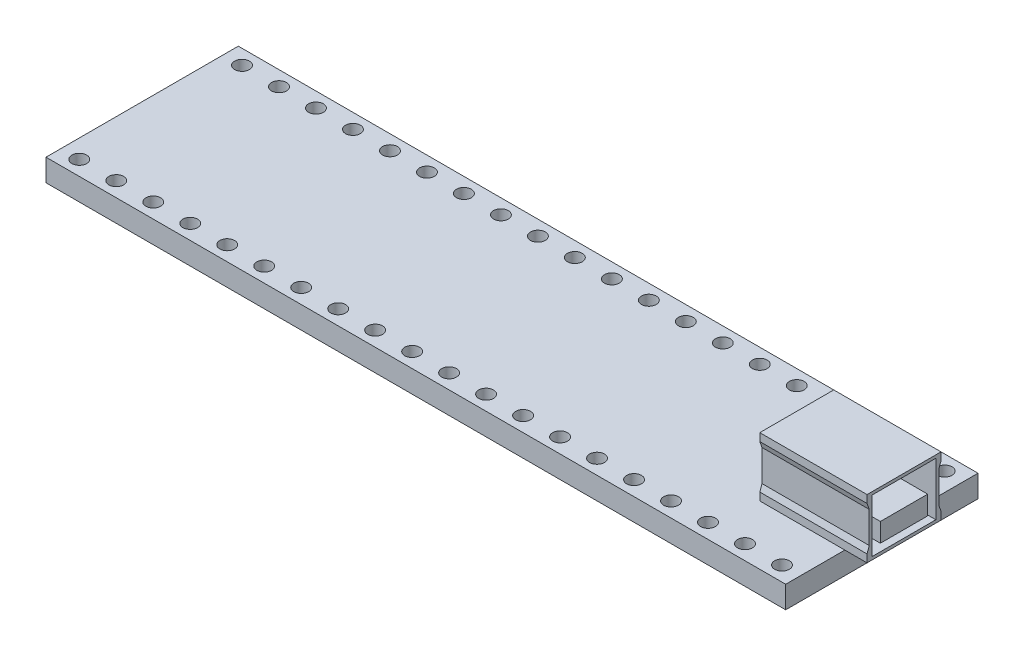
SolidWorks part; units mm, degrees
ref_plane "Спереди" through (0, 0, 0) normal (0, 0, 1) x (1, 0, 0)
ref_plane "Сверху" through (0, 0, 0) normal (0, 1, 0) x (1, 0, 0)
ref_plane "Справа" through (0, 0, 0) normal (1, 0, 0) x (0, 0, -1)
sketch "Эскиз1" plane through (0, 0, 0) normal (0, 1, 0) x (1, 0, 0)
  line L0 (-3.4531, 12) -> (49996.5469, 12) construction
  line L1 (0, 0) -> (50, 0)
  line L2 (0, 0) -> (0, 13)
  line L3 (0, 13) -> (50, 13)
  line L4 (50, 0) -> (50, 13)
  line L5 (-6.0552, 1) -> (49993.9448, 1) construction
  circle A0 centre (1.25, 12) radius 0.5
  circle A1 centre (3.75, 12) radius 0.5
  circle A2 centre (6.25, 12) radius 0.5
  circle A3 centre (8.75, 12) radius 0.5
  circle A4 centre (11.25, 12) radius 0.5
  circle A5 centre (13.75, 12) radius 0.5
  circle A6 centre (16.25, 12) radius 0.5
  circle A7 centre (18.75, 12) radius 0.5
  circle A8 centre (21.25, 12) radius 0.5
  circle A9 centre (23.75, 12) radius 0.5
  circle A10 centre (26.25, 12) radius 0.5
  circle A11 centre (28.75, 12) radius 0.5
  circle A12 centre (31.25, 12) radius 0.5
  circle A13 centre (33.75, 12) radius 0.5
  circle A14 centre (36.25, 12) radius 0.5
  circle A15 centre (3.75, 1) radius 0.5
  circle A16 centre (6.25, 1) radius 0.5
  circle A17 centre (8.75, 1) radius 0.5
  circle A18 centre (11.25, 1) radius 0.5
  circle A19 centre (13.75, 1) radius 0.5
  circle A20 centre (16.25, 1) radius 0.5
  circle A21 centre (18.75, 1) radius 0.5
  circle A22 centre (21.25, 1) radius 0.5
  circle A23 centre (23.75, 1) radius 0.5
  circle A24 centre (26.25, 1) radius 0.5
  circle A25 centre (28.75, 1) radius 0.5
  circle A26 centre (31.25, 1) radius 0.5
  circle A27 centre (33.75, 1) radius 0.5
  circle A28 centre (36.25, 1) radius 0.5
  circle A29 centre (1.25, 1) radius 0.5
  circle A30 centre (38.75, 12) radius 0.5
  circle A31 centre (41.25, 12) radius 0.5
  circle A32 centre (43.75, 12) radius 0.5
  circle A33 centre (46.25, 12) radius 0.5
  circle A34 centre (48.75, 12) radius 0.5
  circle A35 centre (38.75, 1) radius 0.5
  circle A36 centre (41.25, 1) radius 0.5
  circle A37 centre (43.75, 1) radius 0.5
  circle A38 centre (46.25, 1) radius 0.5
  circle A39 centre (48.75, 1) radius 0.5
  dimension "D5" = 1.25
  dimension "D6" = 20
  dimension "D1" = 13
  dimension "D2" = 50
  dimension "D3" = 1
  dimension "D4" = 1
  dimension "D7" = 2
extrude "Бобышка-Вытянуть1" add sketch "Эскиз1" along normal blind 1.5
sketch "Эскиз3" plane through (0, 1.5, 0) normal (0, 1, 0) x (1, 0, 0)
  line L0 (0, 6.5) -> (50, 6.5) construction
  line L1 (44.25, 9) -> (51.5, 9)
  line L2 (44.25, 9) -> (44.25, 4)
  line L3 (44.25, 4) -> (51.5, 4)
  line L4 (51.5, 9) -> (51.5, 4)
  line L5 (0, 13) -> (0, 0) construction
  line L6 (50, 0) -> (50, 13) construction
  dimension "D1" = 2.5
  dimension "D2" = 5
  dimension "D3" = 1.5
  dimension "D4" = 7.25
extrude "Бобышка-Вытянуть2" add sketch "Эскиз3" along normal blind 4
sketch "Эскиз4" plane through (0, 0, 0) normal (0, -1, 0) x (1, 0, 0)
  line L0 (50, 0) -> (50, -13) construction
  line L1 (30.75, -4) -> (38, -4)
  line L2 (30.75, -4) -> (30.75, -9.5)
  line L3 (30.75, -9.5) -> (38, -9.5)
  line L4 (38, -4) -> (38, -9.5)
  point P6 (50, -6.5)
  dimension "D1" = 7.25
  dimension "D2" = 5.5
  dimension "D3" = 12
  dimension "D4" = 2.5
extrude "Бобышка-Вытянуть3" add sketch "Эскиз4" along normal blind 3
sketch "Эскиз5" plane through (51.5, 0, 0) normal (1, 0, 0) x (0, 0, -1)
  line L0 (6.5, 5.5) -> (6.5, 1.5) construction
  line L1 (4, 5.5) -> (9, 5.5) construction
  line L2 (4, 1.5) -> (9, 1.5) construction
  line L4 (4, 4.9769) -> (4.1486, 4.5568)
  line L5 (4, 5.5) -> (4, 1.5) construction
  line L6 (4.1486, 4.5568) -> (4.1486, 3.5404)
  line L7 (4, 3.5) -> (9, 3.5) construction
  line L8 (9, 5.5) -> (9, 1.5) construction
  line L9 (4, 4.9769) -> (4, 5.5)
  line L10 (4, 5.5) -> (9, 5.5)
  line L11 (4, 1.5) -> (9, 1.5)
  line L12 (4, 2.0231) -> (4, 1.5)
  line L13 (4.1486, 2.4432) -> (4.1486, 3.4596)
  line L14 (4, 2.0231) -> (4.1486, 2.4432)
  line L15 (9, 2.0231) -> (8.8514, 2.4432)
  line L16 (8.8514, 2.4432) -> (8.8514, 3.4596)
  line L17 (9, 2.0231) -> (9, 1.5)
  line L18 (9, 4.9769) -> (9, 5.5)
  line L19 (8.8514, 4.5568) -> (8.8514, 3.5404)
  line L20 (9, 4.9769) -> (8.8514, 4.5568)
  line L21 (4.1486, 3.5404) -> (4.1486, 3.4596)
  line L22 (8.8514, 3.5404) -> (8.8514, 3.4596)
  line M2 (9, 1.5) -> (9, 5.5)
  line M4 (4, 5.5) -> (4, 1.5)
extrude "Вырез-Вытянуть1" cut sketch "Эскиз5" against normal up to surface (7.25 mm away) contours L21 L6 L4 L14 L13 M4 | L19 L22 L16 L15 L20 M2 up to face at (44.25, 3.5, -6.5)
sketch "Эскиз6" plane through (51.5, 0, 0) normal (1, 0, 0) x (0, 0, -1)
  line L0 (6.5, 5.5) -> (6.5, 1.5) construction
  line L1 (4, 5.5) -> (9, 5.5) construction
  line L2 (4, 1.5) -> (9, 1.5) construction
  line L3 (4, 1.5) -> (9, 1.5) construction
  line L4 (4.3486, 5.3) -> (8.6514, 5.3)
  line L5 (4.3486, 5.3) -> (4.3486, 1.7)
  line L6 (4.3486, 1.7) -> (8.6514, 1.7)
  line L7 (8.6514, 5.3) -> (8.6514, 1.7)
  line L8 (4.1486, 4.5568) -> (4.1486, 2.4432) construction
  line L9 (8.8514, 4.5568) -> (8.8514, 2.4432) construction
  line L11 (4.9, 3.4745) -> (8.1, 3.4745)
  line L12 (4.9, 3.4745) -> (4.9, 2.2)
  line L13 (4.9, 2.2) -> (8.1, 2.2)
  line L14 (8.1, 3.4745) -> (8.1, 2.2)
  dimension "D1" = 0.2
  dimension "D2" = 0.2
  dimension "D3" = 0.2
  dimension "D4" = 0.2
  dimension "D5" = 3.2
  dimension "D6" = 1.6
  dimension "D7" = 0.5
extrude "Вырез-Вытянуть2" cut sketch "Эскиз6" against normal blind 5
